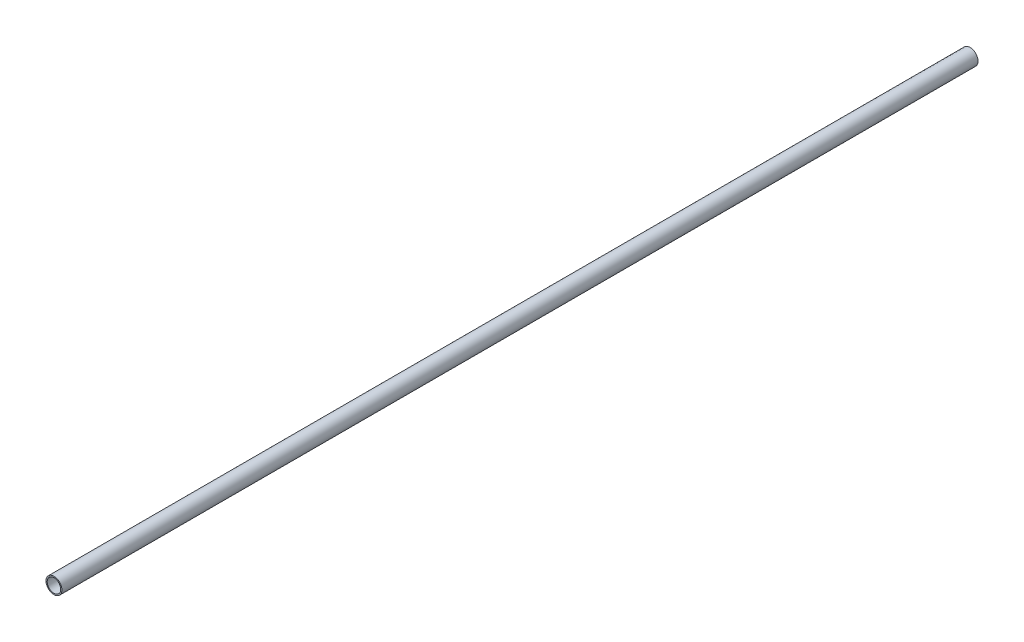
SolidWorks part; units mm, degrees
ref_plane "Front Plane" through (0, 0, 0) normal (0, 0, 1) x (1, 0, 0)
ref_plane "Top Plane" through (0, 0, 0) normal (0, 1, 0) x (1, 0, 0)
ref_plane "Right Plane" through (0, 0, 0) normal (1, 0, 0) x (0, 0, -1)
sketch "Sketch1" plane through (0, 0, 0) normal (0, 0, 1) x (1, 0, 0)
  circle A0 centre (0, 0) radius 15.875
  circle A1 centre (0, 0) radius 13.462
  dimension "D1" = 31.75
  dimension "D2" = 2.413
extrude "Boss-Extrude1" add sketch "Sketch1" along normal blind 1828.8
